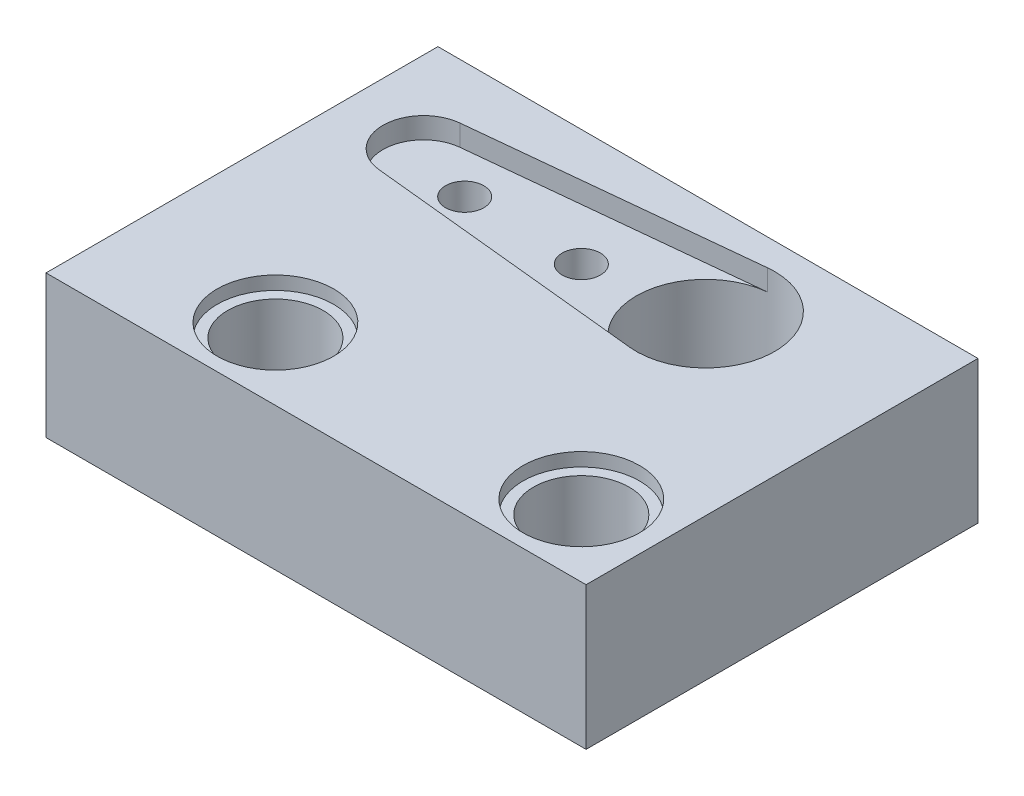
SolidWorks part; units mm, degrees
ref_plane "Front Plane" through (0, 0, 0) normal (0, 0, 1) x (1, 0, 0)
ref_plane "Top Plane" through (0, 0, 0) normal (0, 1, 0) x (1, 0, 0)
ref_plane "Right Plane" through (0, 0, 0) normal (1, 0, 0) x (0, 0, -1)
sketch "Sketch1" plane through (0, 0, 0) normal (0, 1, 0) x (1, 0, 0)
  line L0 (0, 12.1071) -> (0, -10.3651) construction
  line L1 (-19.1976, 0) -> (16.8443, 0) construction
  line L2 (-14.75, 6.703) -> (-14.75, -5.4465) construction
  line L3 (9.25, 15.5) -> (-19, 15.5)
  line L4 (-19, 15.5) -> (-19, -5)
  line L5 (9.25, 15.5) -> (9.25, -5)
  line L6 (-19, 11.75) -> (9.25, 11.75) construction
  line L7 (-4.875, 15.5) -> (-4.875, -5.7439) construction
  line L8 (0, 3.6062) -> (9.25, 3.6062) construction
  line L9 (-14.9661, 2.114) -> (-0.3686, 3.6062) construction
  line L10 (9.25, -4.25) -> (-19, -4.25) construction
  line L11 (-19, -5) -> (9.25, -5)
  circle A0 centre (0, 0) radius 3.625 construction
  circle A1 centre (-14.75, 0) radius 2.125 construction
  circle A2 centre (5.25, 11.75) radius 2.5
  circle A3 centre (-10.75, 11.75) radius 2.5
  point P28 (9.25, 0)
  point P29 (-19, 0)
  dimension "D2" = 7.25
  dimension "D3" = 4.25
  dimension "D7" = 3.75
  dimension "D8" = 5
  dimension "D10" = 5
  dimension "D1" = 14.75
  dimension "D4" = 9.25
  dimension "D5" = 4.25
  dimension "D6" = 15.5
  dimension "D9" = 4
  dimension "D11" = 16
  dimension "D12" = 16
  dimension "D13" = 5
extrude "Boss-Extrude1" add sketch "Sketch1" along normal blind 7.46
sketch "Sketch3" plane through (0, 7.46, 0) normal (0, 1, 0) x (1, 0, 0)
  line L0 (9.25, 0) -> (-19, 0) construction
  line L1 (9.25, -5) -> (9.25, 15.5) construction
  line L2 (-19, 15.5) -> (-19, -5) construction
  line L3 (-19, -5) -> (9.25, -5) construction
  line L4 (-4.875, 15.5) -> (-4.875, -5) construction
  line L5 (9.25, 15.5) -> (-19, 15.5) construction
  line L6 (0, 15.5) -> (0, -5) construction
  line L7 (-14.75, 15.5) -> (-14.75, -5) construction
  line L8 (-14.9655, 2.114) -> (-0.3671, 3.6019)
  line L9 (-14.9655, -2.114) -> (-0.3671, -3.6019)
  arc A0 (-0.3671, -3.6019) -> (-0.3671, 3.6019) centre (0, 0) ccw
  arc A1 (-14.9655, 2.114) -> (-14.9655, -2.114) centre (-14.75, 0) ccw
  dimension "D4" = 4.25
  dimension "D5" = 7.2411
  dimension "D1" = 5
  dimension "D2" = 9.25
  dimension "D3" = 14.75
extrude "Cut-Extrude2" cut sketch "Sketch3" against normal blind 1.1
sketch "Sketch5" plane through (0, 6.36, 0) normal (0, 1, 0) x (1, 0, 0)
  line L0 (0, 3.6205) -> (0, -3.6205) construction
  line L1 (3.6205, 0) -> (-16.875, 0) construction
  line L2 (-6.5, 2.7009) -> (-6.5, -2.6251) construction
  line L3 (-12.6, 1.7656) -> (-12.6, -1.377) construction
  arc A0 (-0.3671, -3.6019) -> (-0.3671, 3.6019) centre (0, 0) ccw construction
  arc A1 (-14.9655, 2.114) -> (-14.9655, -2.114) centre (-14.75, 0) ccw construction
  circle A2 centre (-12.6, 0) radius 1
  circle A3 centre (-6.5, 0) radius 1
  circle A4 centre (0, 0) radius 3.6205
  dimension "D3" = 2
  dimension "D4" = 2
  dimension "D1" = 6.5
  dimension "D2" = 12.6
extrude "Cut-Extrude3" cut sketch "Sketch5" against normal through all
sketch "Sketch6" plane through (0, 7.46, 0) normal (0, 1, 0) x (1, 0, 0)
  circle A0 centre (-10.75, 11.75) radius 3.05
  circle A1 centre (5.25, 11.75) radius 3.05
  dimension "D1" = 6.1
  dimension "D2" = 6.1
extrude "Cut-Extrude4" cut sketch "Sketch6" against normal blind 0.7
sketch "Sketch7" plane through (0, 0, 0) normal (0, -1, 0) x (1, 0, 0)
  circle A0 centre (5.25, -11.75) radius 3.05
  circle A1 centre (-10.75, -11.75) radius 3.05
  dimension "D1" = 6.1
  dimension "D2" = 6.1
extrude "Cut-Extrude5" cut sketch "Sketch7" against normal blind 0.7
sketch "Sketch4" plane through (0, 7.46, 0) normal (0, 1, 0) x (1, 0, 0)
  line L0 (0, 15.5) -> (0, -5) construction
  line L1 (9.25, 15.5) -> (-19, 15.5) construction
  line L2 (-19, -5) -> (9.25, -5) construction
  line L3 (9.25, -5) -> (9.25, 15.5) construction
  line L4 (-14.25, 15.5) -> (-14.25, -5) construction
  dimension "D1" = 9.25
  dimension "D2" = 14.25
mirror "Mirror2" about plane through (9.25, 7.46, -15.5) normal (0, 0, 1) of bodies 106
delete or keep bodies "Body-Delete/Keep 1" type delete bodies bodies 106
